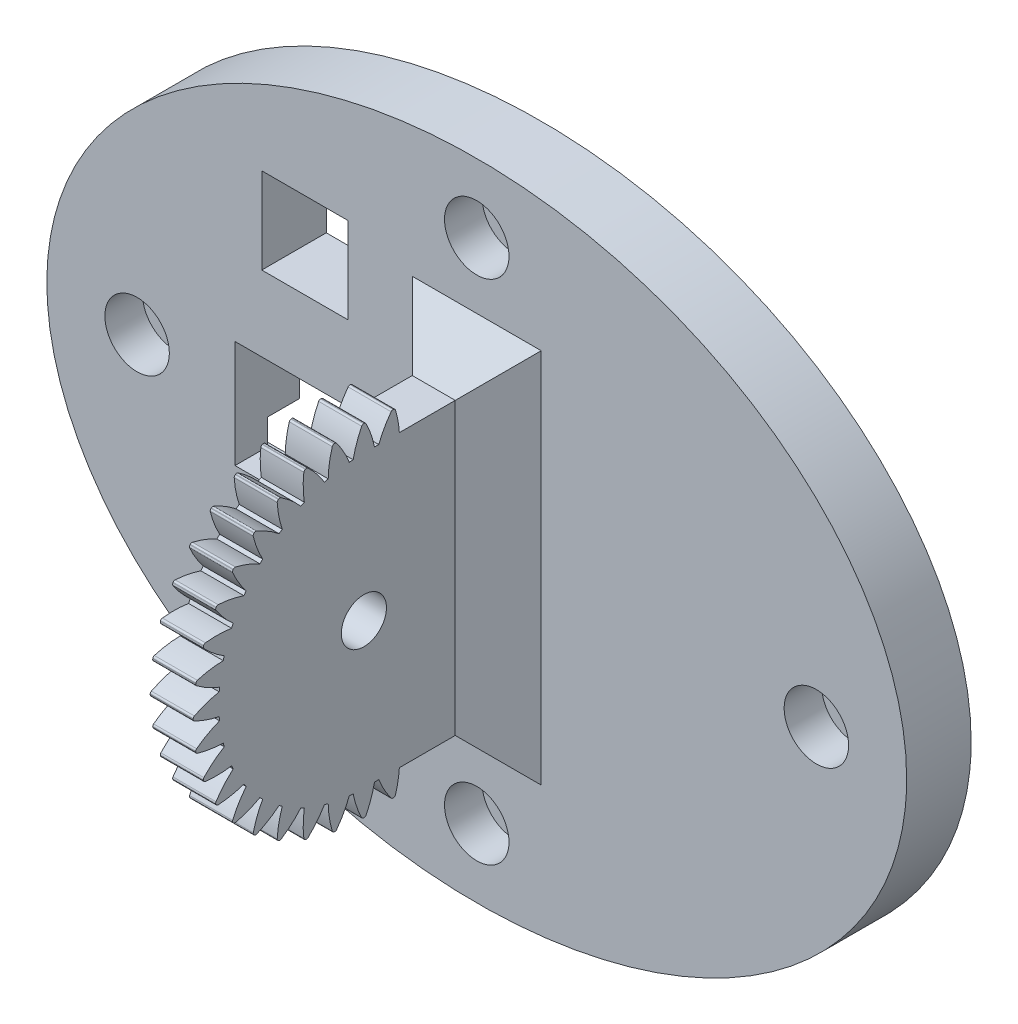
SolidWorks part; units mm, degrees
material "PET"
ref_plane "Front Plane" through (0, 0, 0) normal (0, 0, 1) x (1, 0, 0)
ref_plane "Top Plane" through (0, 0, 0) normal (0, 1, 0) x (1, 0, 0)
ref_plane "Right Plane" through (0, 0, 0) normal (1, 0, 0) x (0, 0, -1)
sketch "Sketch2" plane through (0, 0, 0) normal (0, 0, 1) x (1, 0, 0)
  ellipse E0 centre (0, 0) end of major axis (50.8, 0) minor radius 38.1
  dimension "D1" = 101.6
  dimension "D2" = 76.2
extrude "Boss-Extrude1" add sketch "Sketch2" along normal blind 7.62
ref_plane "Plane1" through (0, 0, 12.7) normal (0, 0, 1) x (1, 0, 0)
sketch "Sketch6" plane through (0, 0, 7.62) normal (0, 0, 1) x (1, 0, 0)
  line L0 (0, 38.1) -> (0, 29.972) construction
  circle A0 centre (0, 29.972) radius 2.2225
  ellipse E0 centre (0, 0) end of major axis (50.8, 0) minor radius 38.1 construction
  ellipse E1 centre (0, 0) end of major axis (50.8, 0) minor radius 38.1
  dimension "D2" = 4.445
  dimension "D1" = 8.128
extrude "Cut-Extrude1" cut sketch "Sketch6" against normal through all
sketch "Sketch7" plane through (0, 0, 7.62) normal (0, 0, 1) x (1, 0, 0)
  circle A0 centre (0, 29.972) radius 3.81
  dimension "D1" = 7.62
extrude "Cut-Extrude2" cut sketch "Sketch7" against normal blind 4.445
mirror "Mirror1" about plane through (0, 0, 0) normal (0, 1, 0) of "Cut-Extrude2", "Cut-Extrude1"
sketch "Sketch8" plane through (0, 0, 7.62) normal (0, 0, 1) x (1, 0, 0)
  line L0 (-50.8, 0) -> (-40.132, 0) construction
  circle A0 centre (-40.132, 0) radius 2.2225
  ellipse E0 centre (0, 0) end of major axis (50.8, 0) minor radius 38.1 construction
  dimension "D2" = 4.445
  dimension "D1" = 10.668
extrude "Cut-Extrude3" cut sketch "Sketch8" against normal through all
sketch "Sketch9" plane through (0, 0, 7.62) normal (0, 0, 1) x (1, 0, 0)
  circle A0 centre (-40.132, 0) radius 3.81
  dimension "D1" = 7.62
extrude "Cut-Extrude4" cut sketch "Sketch9" against normal blind 4.445
mirror "Mirror2" about plane through (0, 0, 0) normal (1, 0, 0) of "Cut-Extrude4", "Cut-Extrude3"
sketch "Sketch10" plane through (0, 0, 7.62) normal (0, 0, 1) x (1, 0, 0)
  line L0 (-36.322, 0) -> (36.322, 0)
  line L2 (-2.54, 17.145) -> (2.54, 17.145)
  line L3 (-2.54, 17.145) -> (-2.54, -17.145)
  line L4 (-2.54, -17.145) -> (2.54, -17.145)
  line L5 (2.54, 17.145) -> (2.54, -17.145)
  line L6 (-2.54, 17.145) -> (2.54, -17.145) construction
  line L7 (-2.54, -17.145) -> (2.54, 17.145) construction
  circle A0 centre (40.132, 0) radius 3.81 construction
  point P4 (0, 0)
  point P12 (0, 0)
  dimension "D1" = 5.08
  dimension "D3" = 34.29
extrude "Boss-Extrude2" add sketch "Sketch10" along normal blind 15.875
chamfer "Chamfer1" distance 5.08 angle 45 4 edges at (2.54, 0, 7.62) (-2.54, 0, 7.62) (0, -17.145, 7.62) (0, 17.145, 7.62)
sketch "Sketch11" plane through (-2.54, 0, 0) normal (-1, 0, 0) x (0, 0, 1)
  line L0 (23.495, 17.145) -> (23.495, -17.145) construction
  circle A0 centre (23.495, 0) radius 2.667
  dimension "D2" = 5.334
extrude "Cut-Extrude5" cut sketch "Sketch11" against normal through all
sketch "Sketch14" plane through (-2.54, 0, 0) normal (-1, 0, 0) x (0, 0, 1)
  circle A0 centre (23.495, 0) radius 17.145
  circle A1 centre (23.495, 0) radius 2.667
  circle A2 centre (23.495, 0) radius 2.667 construction
  dimension "D1" = 34.29
extrude "Boss-Extrude3" add sketch "Sketch14" against normal up to surface (5.08 mm away) up to face at (2.54, 0, 19.4522)
sketch "Sketch13" plane through (-2.54, 0, 0) normal (-1, 0, 0) x (0, 0, 1)
  line L0 (24.13, 0) -> (33.02, 0) construction
  line L2 (43.6626, 0.0351) -> (43.6626, -0.0351)
  arc A2 (40.5674, 1.27) -> (43.5227, 0.262) centre (38.3898, -9.9507) cw
  arc A3 (40.5674, -1.27) -> (43.5227, -0.262) centre (38.3898, 9.9507) ccw
  arc A6 (23.495, -17.1196) -> (23.495, 17.1196) centre (23.495, 0) ccw
  arc A7 (40.5674, -1.27) -> (40.5674, 1.27) centre (23.495, 0) ccw
  arc A8 (43.5227, -0.262) -> (43.6626, -0.0351) centre (43.4086, -0.0351) ccw
  arc A9 (43.6626, 0.0351) -> (43.5227, 0.262) centre (43.4086, 0.0351) ccw
  point P4 (43.6626, -0.1905)
  point P10 (40.6146, 0)
  point P12 (43.6626, 0.1905)
  point P19 (43.6626, 0)
  point P23 (43.6626, -0.1905)
  point P26 (43.6626, 0.1905)
  dimension "D1" = 0.0254
  dimension "D2" = 11.43
  dimension "D6" = 0.254
  dimension "D3" = 3.048
  dimension "D4" = 1.27
  dimension "D5" = 0.1905
extrude "Boss-Extrude4" add sketch "Sketch13" against normal up to surface (5.08 mm away) up to face at (2.54, 0, 22.3837)
pattern_circular "CirPattern1" count 36 over 360 about axis through (0, 0, 23.495) along (1, 0, 0) of "Boss-Extrude4"
sketch "Sketch16" plane through (0, 0, 7.62) normal (0, 0, 1) x (1, 0, 0)
  line L0 (-50.8, 0) -> (50.8, 0) construction
  line L1 (-50.7718, -1.27) -> (50.7718, -1.27) construction
  line L2 (0, 38.1) -> (0, -38.1) construction
  line L3 (-21.8948, 5.08) -> (-21.8948, -7.62) construction
  line L4 (-28.5623, 5.08) -> (-15.2273, 5.08)
  line L5 (-28.5623, 5.08) -> (-28.5623, -7.62)
  line L6 (-28.5623, -7.62) -> (-15.2273, -7.62)
  line L7 (-15.2273, 5.08) -> (-15.2273, -7.62)
  line L8 (2.5273, 4.8895) -> (13.3223, 4.8895) construction
  line L9 (2.5273, 4.8895) -> (2.5273, -7.4295) construction
  line L10 (2.5273, -7.4295) -> (13.3223, -7.4295) construction
  line L11 (13.3223, 4.8895) -> (13.3223, -7.4295) construction
  line L12 (7.9248, 4.8895) -> (7.9248, -7.4295) construction
  line L13 (-15.2273, 1.27) -> (2.5273, 1.27) construction
  line L14 (-6.35, 1.27) -> (-6.35, 0) construction
  ellipse E0 centre (0, 0) end of major axis (50.8, 0) minor radius 38.1 construction
  point P25 (-28.5623, -1.27)
  point P26 (13.3223, -1.27)
  dimension "D1" = 1.27
  dimension "D2" = 13.335
  dimension "D3" = 12.7
  dimension "D4" = 10.795
  dimension "D5" = 17.7546
  dimension "D6" = 1.27
  dimension "D7" = 6.35
  dimension "D8" = 17.7546
  dimension "D9" = 12.319
extrude "Cut-Extrude7" cut sketch "Sketch16" against normal blind 7.62
sketch "Sketch17" plane through (0, 0, 0) normal (0, 0, -1) x (-1, 0, 0)
  line L0 (0, 0) -> (0, 27.7495) construction
  line L8 (-18.4277, -10.922) -> (39.9923, -10.922)
  line L9 (-18.4277, -10.922) -> (-18.4277, -4.572)
  line L10 (-18.4277, -4.572) -> (39.9923, -4.572)
  line L11 (39.9923, -10.922) -> (39.9923, -4.572)
  line L12 (10.7823, -4.572) -> (10.7823, -10.922) construction
  line L13 (28.5623, 5.08) -> (28.5623, -7.62) construction
  line L14 (28.5623, -7.62) -> (15.2273, -7.62) construction
  circle A0 centre (0, 29.972) radius 2.2225 construction
  dimension "D1" = 11.43
  dimension "D2" = 3.048
  dimension "D4" = 58.42
  dimension "D5" = 6.35
extrude "Cut-Extrude8" cut sketch "Sketch17" against normal blind 3.81
sketch "Sketch19" plane through (0, 0, 0) normal (0, 0, -1) x (-1, 0, 0)
  line L0 (15.2273, 5.08) -> (-50.3464, 5.08) construction
  line L1 (15.2273, -4.572) -> (15.2273, 5.08) construction
  line L2 (-13.2969, 5.08) -> (-2.5019, 5.08)
  line L3 (-13.2969, 5.08) -> (-13.2969, -7.62)
  line L4 (-13.2969, -7.62) -> (-2.5019, -7.62)
  line L5 (-2.5019, 5.08) -> (-2.5019, -7.62)
  ellipse E0 centre (0, 0) end of major axis (-50.8, 0) minor radius 38.1 construction
  dimension "D1" = 10.795
  dimension "D2" = 12.7
  dimension "D3" = 17.7292
extrude "Cut-Extrude9" cut sketch "Sketch19" against normal blind 5.842
sketch "Sketch21" plane through (0, 0, 7.62) normal (0, 0, 1) x (1, 0, 0)
  line L0 (-20.32, 24.13) -> (-20.32, 13.97) construction
  line L1 (-25.4, 24.13) -> (-15.24, 24.13)
  line L2 (-25.4, 24.13) -> (-25.4, 13.97)
  line L3 (-25.4, 13.97) -> (-15.24, 13.97)
  line L4 (-15.24, 24.13) -> (-15.24, 13.97)
  line L5 (-25.4, 19.05) -> (-15.24, 19.05) construction
  point P9 (-20.32, 19.05)
  dimension "D1" = 10.16
  dimension "D2" = 10.16
  dimension "D3" = 20.32
  dimension "D4" = 19.05
extrude "Cut-Extrude11" cut sketch "Sketch21" against normal blind 10.16
sketch "Sketch22" plane through (-2.54, 0, 0) normal (-1, 0, 0) x (0, 0, 1)
  line L0 (12.7, 0) -> (20.828, 0) construction
  line L1 (19.3026, 17.145) -> (12.9526, 17.145)
  line L2 (19.3026, 17.145) -> (19.3026, 19.685)
  line L3 (19.3026, 19.685) -> (12.9526, 19.685)
  line L4 (12.9526, 17.145) -> (12.9526, 19.685)
  line L5 (12.7, 17.145) -> (12.7, -17.145) construction
  line L6 (19.3026, -19.685) -> (12.9526, -19.685)
  line L7 (12.9526, -17.145) -> (12.9526, -19.685)
  line L8 (19.3026, -17.145) -> (12.9526, -17.145)
  line L9 (19.3026, -17.145) -> (19.3026, -19.685)
  circle A0 centre (23.495, 0) radius 2.667 construction
  dimension "D1" = 6.35
  dimension "D2" = 2.54
extrude "Cut-Extrude12" cut sketch "Sketch22" against normal up to surface (5.08 mm away) up to face at (2.54, 0, 30.4085)
equation "\"ft\"=0.24"
